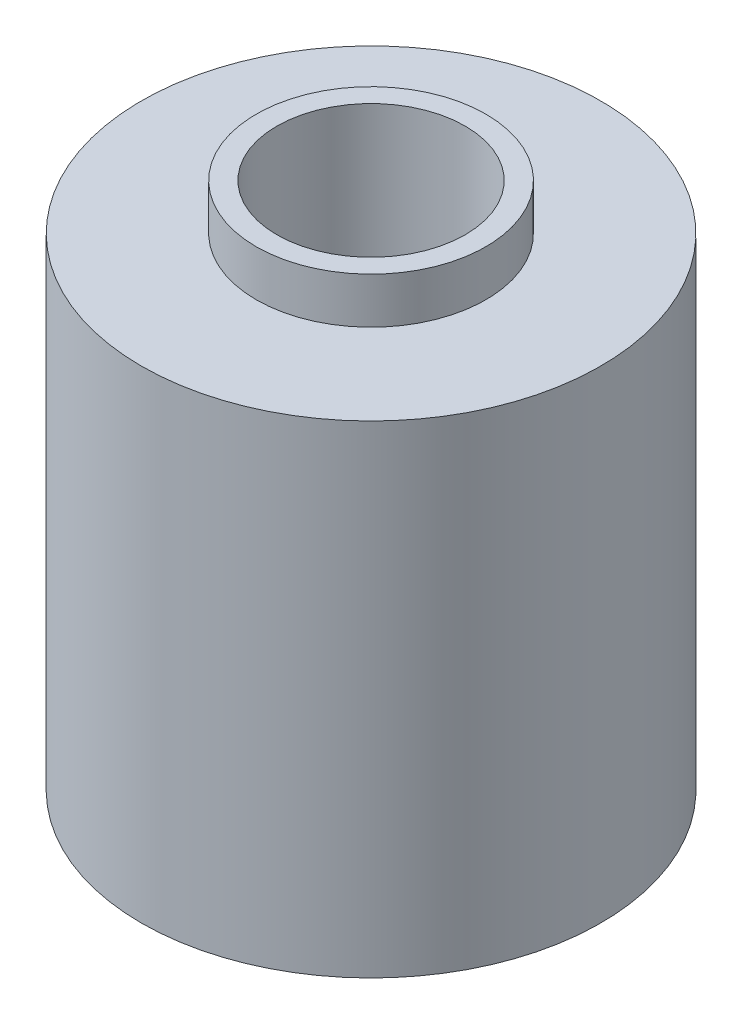
SolidWorks part; units mm, degrees
ref_plane "Front Plane" through (0, 0, 0) normal (0, 0, 1) x (1, 0, 0)
ref_plane "Top Plane" through (0, 0, 0) normal (0, 1, 0) x (1, 0, 0)
ref_plane "Right Plane" through (0, 0, 0) normal (1, 0, 0) x (0, 0, -1)
sketch "Sketch1" plane through (0, 0, 0) normal (1, 0, 0) x (0, 0, -1)
  line L0 (0, 30.4346) -> (0, -34.3769) construction
  line L1 (4.1, 12.5) -> (4.1, -12.5)
  line L2 (4.1, 12.5) -> (5, 12.5)
  line L3 (5, 12.5) -> (5, 10.5)
  line L4 (5, 10.5) -> (10, 10.5)
  line L5 (10, 10.5) -> (10, -10.5)
  line L6 (10, -10.5) -> (5, -10.5)
  line L7 (5, -10.5) -> (5, -12.5)
  line L8 (5, -12.5) -> (4.1, -12.5)
  point P5 (4.1, 0)
  point P6 (10, 0)
  dimension "D1" = 4.1
  dimension "D2" = 5
  dimension "D3" = 10
  dimension "D4" = 21
  dimension "D5" = 2
revolve "Revolve1" add sketch "Sketch1" angle 360 about L0
